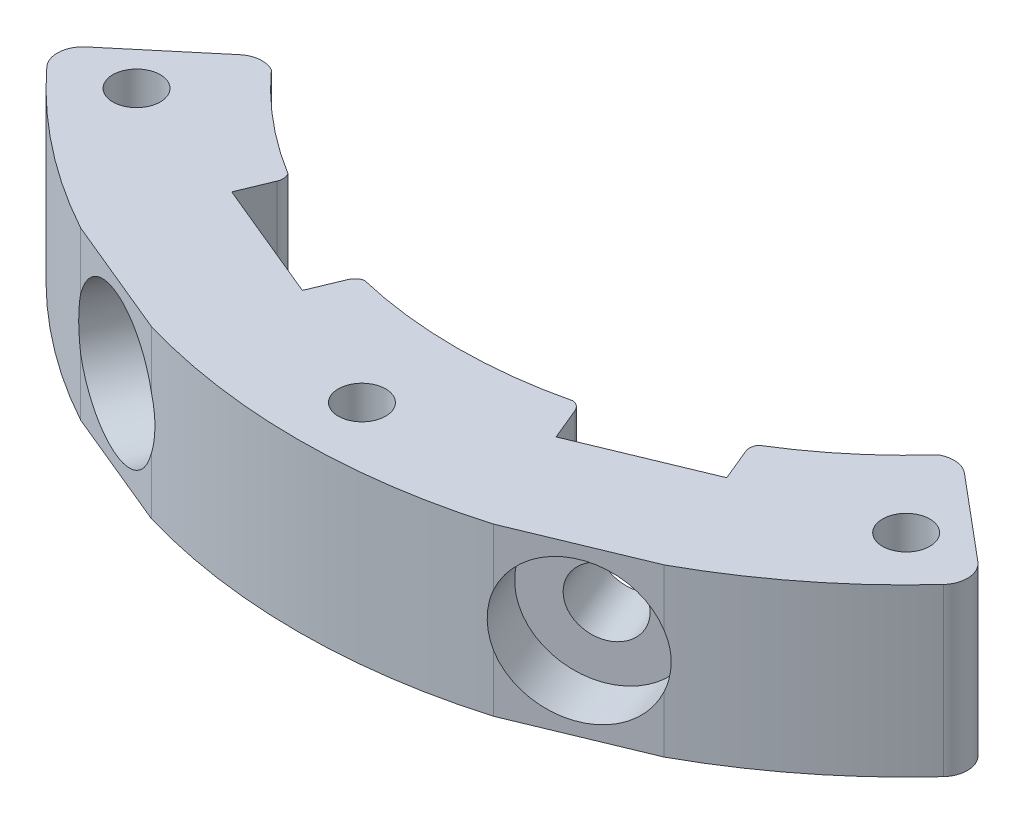
SolidWorks part; units mm, degrees
ref_plane "前视基准面" through (0, 0, 0) normal (0, 0, 1) x (1, 0, 0)
ref_plane "上视基准面" through (0, 0, 0) normal (0, 1, 0) x (1, 0, 0)
ref_plane "右视基准面" through (0, 0, 0) normal (1, 0, 0) x (0, 0, -1)
other "Configuration Table"
sketch "草图1" plane through (0, 0, 0) normal (0, 1, 0) x (1, 0, 0)
  line L0 (0, 0) -> (-42.5, 0) construction
  line L1 (0, 0) -> (0, -42.5) construction
  line L2 (0, 0) -> (-32.5569, -27.3185) construction
  line L3 (-26.8116, -22.4976) -> (-36.3871, -30.5324)
  line L4 (0, 0) -> (-15.026, -36.276) construction
  line L5 (-30.052, -30.052) -> (0, -42.5)
  line L6 (-17.9627, -30.039) -> (-19.3303, -33.3405)
  line L7 (-19.3303, -33.3405) -> (-9.9067, -37.2439)
  line L8 (-9.9067, -37.2439) -> (-8.5392, -33.9423)
  line L9 (9.9067, -37.2439) -> (8.5392, -33.9423)
  line L10 (19.3303, -33.3405) -> (9.9067, -37.2439)
  line L11 (17.9627, -30.039) -> (19.3303, -33.3405)
  line L12 (26.8116, -22.4976) -> (36.3871, -30.5324)
  circle A0 centre (0, 0) radius 42.5 construction
  circle A1 centre (0, -42.5) radius 1.85
  circle A2 centre (0, 0) radius 35
  circle A3 centre (0, 0) radius 47.5
  circle A4 centre (-30.052, -30.052) radius 1.85
  circle A5 centre (30.052, -30.052) radius 1.85
  point P18 (-14.6185, -35.2922)
  dimension "D1" = 85
  dimension "D2" = 3.7
  dimension "D4" = 95
  dimension "D5" = 70
  dimension "D7" = 3.7
  dimension "D3" = 40
  dimension "D6" = 22.5
  dimension "D8" = 38.2
  dimension "D9" = 10.2
extrude "凸台-拉伸1" add sketch "草图1" along normal blind 13
sketch "草图2" plane through (-14.6185, 0, 35.2922) normal (0.3827, 0, -0.9239) x (-0.9239, 0, -0.3827)
  line L0 (0, 13) -> (0, 0) construction
  line L1 (-5.1, 6.5) -> (5.1, 6.5) construction
  line L4 (-5.1, 0) -> (5.1, 0)
  line L5 (5.1, 0) -> (5.1, 13)
  line L6 (5.1, 13) -> (-5.1, 13)
  line L7 (-5.1, 13) -> (-5.1, 0)
  line L8 (-5.1, 0) -> (5.1, 0)
  line L9 (5.1, 0) -> (5.1, 13)
  line L10 (5.1, 13) -> (-5.1, 13)
  line L11 (-5.1, 13) -> (-5.1, 0)
  circle A0 centre (0, 6.5) radius 2.6
  dimension "D2" = 5.2
  dimension "D1" = 0
extrude "切除-拉伸1" cut sketch "草图2" against normal blind 10 contours A0
sketch "草图3" plane through (14.6185, 0, 35.2922) normal (-0.3827, 0, -0.9239) x (-0.9239, 0, 0.3827)
  line L0 (0, 13) -> (0, 0) construction
  line L1 (-5.1, 6.5) -> (5.1, 6.5) construction
  line L4 (-5.1, 0) -> (5.1, 0)
  line L5 (5.1, 0) -> (5.1, 13)
  line L6 (5.1, 13) -> (-5.1, 13)
  line L7 (-5.1, 13) -> (-5.1, 0)
  line L8 (-5.1, 0) -> (5.1, 0)
  line L9 (5.1, 0) -> (5.1, 13)
  line L10 (5.1, 13) -> (-5.1, 13)
  line L11 (-5.1, 13) -> (-5.1, 0)
  circle A0 centre (0, 6.5) radius 2.6
  dimension "D2" = 5.2
  dimension "D1" = 0
extrude "切除-拉伸2" cut sketch "草图3" against normal blind 10 contours A0
fillet "圆角1" radius 2 4 edges at (26.8116, 6.5, 22.4976) (36.3871, 6.5, 30.5324) (-26.8116, 6.5, 22.4976) (-36.3871, 6.5, 30.5324)
fillet "圆角2" radius 1 4 edges at (-8.5392, 6.5, 33.9423) (-17.9627, 6.5, 30.039) (17.9627, 6.5, 30.039) (8.5392, 6.5, 33.9423)
sketch "草图4" plane through (0, 0, 0) normal (0, -1, 0) x (1, 0, 0)
  circle A0 centre (-30.052, 30.052) radius 3.5
  circle A1 centre (0, 42.5) radius 1.85
  circle A2 centre (0, 42.5) radius 1.85
  circle A3 centre (-30.052, 30.052) radius 1.85
  circle A4 centre (-30.052, 30.052) radius 1.85
  circle A5 centre (30.052, 30.052) radius 1.85
  circle A6 centre (30.052, 30.052) radius 1.85
  circle A7 centre (0, 42.5) radius 3.5
  circle A8 centre (30.052, 30.052) radius 3.5
  dimension "D4" = 7
  dimension "D5" = 7
  dimension "D6" = 7
  dimension "D1" = 0
  dimension "D2" = 0
  dimension "D3" = 0
extrude "切除-拉伸3" cut sketch "草图4" against normal blind 7
sketch "草图5" plane through (0, 0, 0) normal (0, -1, 0) x (1, 0, 0)
  line L0 (-14.6185, 35.2922) -> (-18.1775, 43.8843)
  line L1 (14.6185, 35.2922) -> (18.1775, 43.8843)
  line L2 (-22.7842, 41.6789) -> (-13.3606, 45.5823)
  line L3 (-19.3303, 33.3405) -> (-22.7842, 41.6789)
  line L4 (-9.9067, 37.2439) -> (-13.3606, 45.5823)
  line L5 (0, 42.5) -> (0, 0)
  line L6 (22.7842, 41.6789) -> (13.3606, 45.5823)
  line L8 (-9.9067, 37.2439) -> (-8.8656, 34.7304)
  line L9 (8.8656, 34.7304) -> (9.9067, 37.2439)
  line L10 (9.9067, 37.2439) -> (19.3303, 33.3405)
  line L11 (19.3303, 33.3405) -> (18.2892, 30.827)
  line L12 (28.3022, 23.7484) -> (34.8213, 29.2186)
  line L13 (-34.8213, 29.2186) -> (-28.3022, 23.7484)
  line L14 (-18.2892, 30.827) -> (-19.3303, 33.3405)
  line L15 (-19.3303, 33.3405) -> (-9.9067, 37.2439)
  line L16 (-9.9067, 37.2439) -> (-8.8656, 34.7304)
  line L17 (8.8656, 34.7304) -> (9.9067, 37.2439)
  line L18 (9.9067, 37.2439) -> (19.3303, 33.3405)
  line L19 (19.3303, 33.3405) -> (18.2892, 30.827)
  line L20 (28.3022, 23.7484) -> (34.8213, 29.2186)
  line L21 (-34.8213, 29.2186) -> (-28.3022, 23.7484)
  line L22 (-18.2892, 30.827) -> (-19.3303, 33.3405)
  line L23 (-19.3303, 33.3405) -> (-9.9067, 37.2439)
  arc A0 (35.0099, 32.1023) -> (-35.0099, 32.1023) centre (0, 0) ccw construction
  arc A12 (-8.8656, 34.7304) -> (-7.7211, 34.1377) centre (-7.9417, 35.1131) ccw
  arc A13 (7.7211, 34.1377) -> (-7.7211, 34.1377) centre (0, 0) ccw
  arc A14 (7.7211, 34.1377) -> (8.8656, 34.7304) centre (7.9417, 35.1131) ccw
  arc A15 (18.2892, 30.827) -> (18.6794, 29.5987) centre (19.2131, 30.4444) ccw
  arc A16 (25.5563, 23.9139) -> (18.6794, 29.5987) centre (0, 0) ccw
  arc A17 (25.5563, 23.9139) -> (28.3022, 23.7484) centre (27.0166, 25.2805) ccw
  arc A18 (34.8213, 29.2186) -> (35.0099, 32.1023) centre (33.5358, 30.7507) ccw
  arc A19 (35.0099, 32.1023) -> (-35.0099, 32.1023) centre (0, 0) ccw
  arc A20 (-35.0099, 32.1023) -> (-34.8213, 29.2186) centre (-33.5358, 30.7507) ccw
  arc A21 (-28.3022, 23.7484) -> (-25.5563, 23.9139) centre (-27.0166, 25.2805) ccw
  arc A22 (-18.6794, 29.5987) -> (-25.5563, 23.9139) centre (0, 0) ccw
  arc A23 (-18.6794, 29.5987) -> (-18.2892, 30.827) centre (-19.2131, 30.4444) ccw
  arc A24 (-8.8656, 34.7304) -> (-7.7211, 34.1377) centre (-7.9417, 35.1131) ccw
  arc A25 (7.7211, 34.1377) -> (-7.7211, 34.1377) centre (0, 0) ccw
  arc A26 (7.7211, 34.1377) -> (8.8656, 34.7304) centre (7.9417, 35.1131) ccw
  arc A27 (18.2892, 30.827) -> (18.6794, 29.5987) centre (19.2131, 30.4444) ccw
  arc A28 (25.5563, 23.9139) -> (18.6794, 29.5987) centre (0, 0) ccw
  arc A29 (25.5563, 23.9139) -> (28.3022, 23.7484) centre (27.0166, 25.2805) ccw
  arc A30 (34.8213, 29.2186) -> (35.0099, 32.1023) centre (33.5358, 30.7507) ccw
  arc A31 (35.0099, 32.1023) -> (-35.0099, 32.1023) centre (0, 0) ccw
  arc A32 (-35.0099, 32.1023) -> (-34.8213, 29.2186) centre (-33.5358, 30.7507) ccw
  arc A33 (-28.3022, 23.7484) -> (-25.5563, 23.9139) centre (-27.0166, 25.2805) ccw
  arc A34 (-18.6794, 29.5987) -> (-25.5563, 23.9139) centre (0, 0) ccw
  arc A35 (-18.6794, 29.5987) -> (-18.2892, 30.827) centre (-19.2131, 30.4444) ccw
  arc M39 (35.0099, 32.1023) -> (-35.0099, 32.1023) centre (0, 0) ccw
  dimension "D1" = 0
extrude "切除-拉伸5" cut sketch "草图5" against normal through all contours L2 L0 M39 | L0 L2 M39 | L6 L1 M39 | L6 L1 M39
sketch "草图6" plane through (-18.0724, 0, 43.6306) normal (-0.3827, 0, 0.9239) x (0.9239, 0, 0.3827)
  circle A0 centre (0, 6.5) radius 2.6 construction
  circle A1 centre (0, 6.5) radius 2.6
  circle A2 centre (0, 6.5) radius 5.5
  dimension "D1" = 11
extrude "切除-拉伸6" cut sketch "草图6" against normal blind 4
sketch "草图7" plane through (18.0724, 0, 43.6306) normal (0.3827, 0, 0.9239) x (0.9239, 0, -0.3827)
  circle A0 centre (0, 6.5) radius 2.6 construction
  circle A1 centre (0, 6.5) radius 2.6
  circle A2 centre (0, 6.5) radius 5.5
  dimension "D1" = 11
extrude "切除-拉伸7" cut sketch "草图7" against normal blind 4
sketch "草图8" plane through (0, 13, 0) normal (0, 1, 0) x (1, 0, 0)
  circle A0 centre (0, 0) radius 35.1
  dimension "D1" = 70.2
extrude "切除-拉伸8" cut sketch "草图8" against normal through all contours A0
